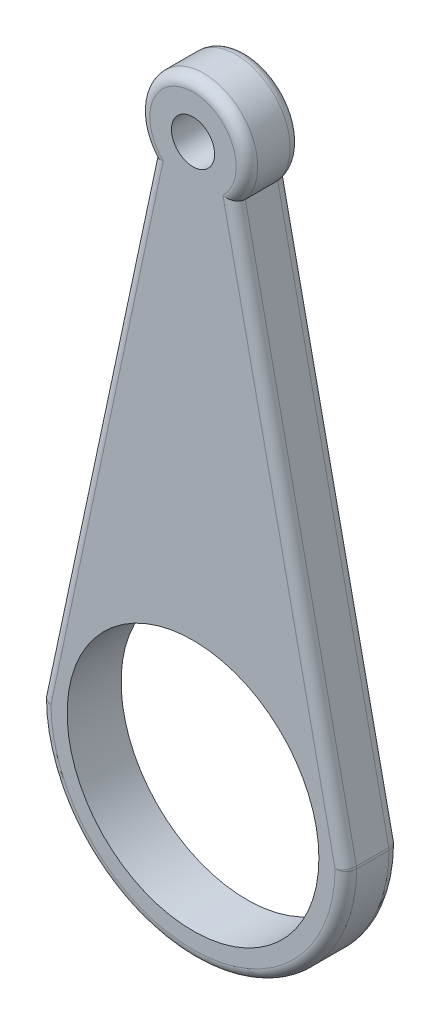
SolidWorks part; units mm, degrees
ref_plane "Front Plane" through (0, 0, 0) normal (0, 0, 1) x (1, 0, 0)
ref_plane "Top Plane" through (0, 0, 0) normal (0, 1, 0) x (1, 0, 0)
ref_plane "Right Plane" through (0, 0, 0) normal (1, 0, 0) x (0, 0, -1)
sketch "Sketch1" plane through (0, 0, 0) normal (0, 0, 1) x (1, 0, 0)
  line L0 (0, 0) -> (0, 155)
  line L1 (0, 0) -> (50000, 0) construction
  line L2 (-42.5, 0) -> (-11.5447, 145.4229)
  line L3 (42.5, 0) -> (11.5447, 145.4229)
  arc A0 (-42.5, 0) -> (42.5, 0) centre (0, 0) ccw
  circle A1 centre (0, 155) radius 10 construction
  arc A2 (11.5447, 145.4229) -> (-11.5447, 145.4229) centre (0, 155) ccw
  circle A3 centre (0, 0) radius 35
  circle A4 centre (0, 155) radius 6
  dimension "D1" = 85
  dimension "D3" = 20
  dimension "D4" = 30
  dimension "D7" = 70
  dimension "D8" = 12
  dimension "D2" = 155
  dimension "D5" = 145.4229
  dimension "D6" = 145.4229
extrude "Boss-Extrude1" add sketch "Sketch1" along normal mid plane 15
fillet "Fillet1" radius 3 10 edges at (0, -42.5, -7.5) (-27.0223, 72.7115, -7.5) (0, 170, -7.5) (27.0223, 72.7115, -7.5) (-27.0223, 72.7115, 7.5) (0, -42.5, 7.5) (27.0223, 72.7115, 7.5) (0, 170, 7.5) (42.5, 0, 0) (-42.5, 0, 0)
